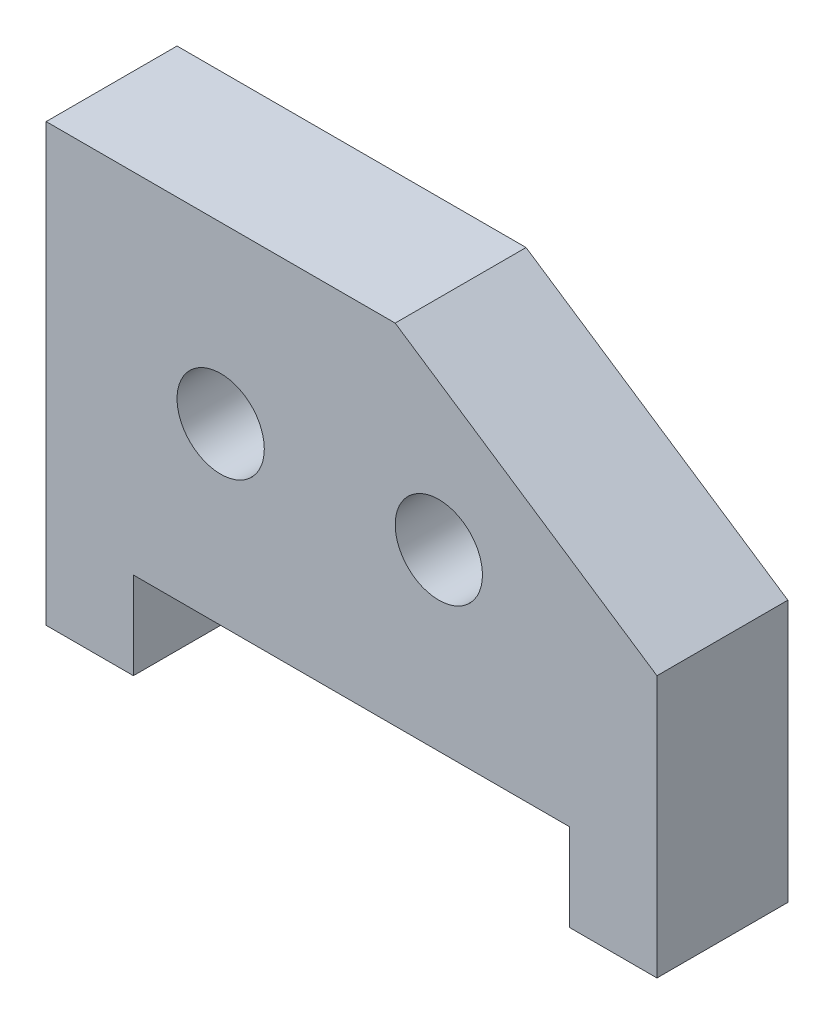
SolidWorks part; units mm, degrees
ref_plane "Front Plane" through (0, 0, 0) normal (0, 0, 1) x (1, 0, 0)
ref_plane "Top Plane" through (0, 0, 0) normal (0, 1, 0) x (1, 0, 0)
ref_plane "Right Plane" through (0, 0, 0) normal (1, 0, 0) x (0, 0, -1)
sketch "Sketch1" plane through (0, 0, 0) normal (0, 0, 1) x (1, 0, 0)
  line L0 (54.1667, 104.1667) -> (204.1667, 4.1667)
  line L1 (-145.8333, -145.8333) -> (-95.8333, -145.8333)
  line L2 (-145.8333, -145.8333) -> (-145.8333, 104.1667)
  line L3 (-145.8333, 104.1667) -> (54.1667, 104.1667)
  line L4 (204.1667, -145.8333) -> (204.1667, 4.1667)
  line L5 (-145.8333, -145.8333) -> (84.1667, 84.1667) construction
  line L6 (-145.8333, 104.1667) -> (204.1667, -145.8333) construction
  line L7 (154.1667, -145.8333) -> (154.1667, -95.8333)
  line L8 (154.1667, -95.8333) -> (-95.8333, -95.8333)
  line L9 (-95.8333, -95.8333) -> (-95.8333, -145.8333)
  line L10 (154.1667, -145.8333) -> (204.1667, -145.8333)
  circle A0 centre (79.1667, 4.1667) radius 25
  circle A1 centre (-45.8333, 4.1667) radius 25
  point P0 (0, 0)
  dimension "D8" = 125
  dimension "D1" = 350
  dimension "D2" = 250
  dimension "D3" = 200
  dimension "D4" = 150
  dimension "D5" = 250
  dimension "D6" = 50
  dimension "D7" = 50
  dimension "D9" = 100
  dimension "D10" = 100
extrude "Boss-Extrude1" add sketch "Sketch1" along normal blind 75
